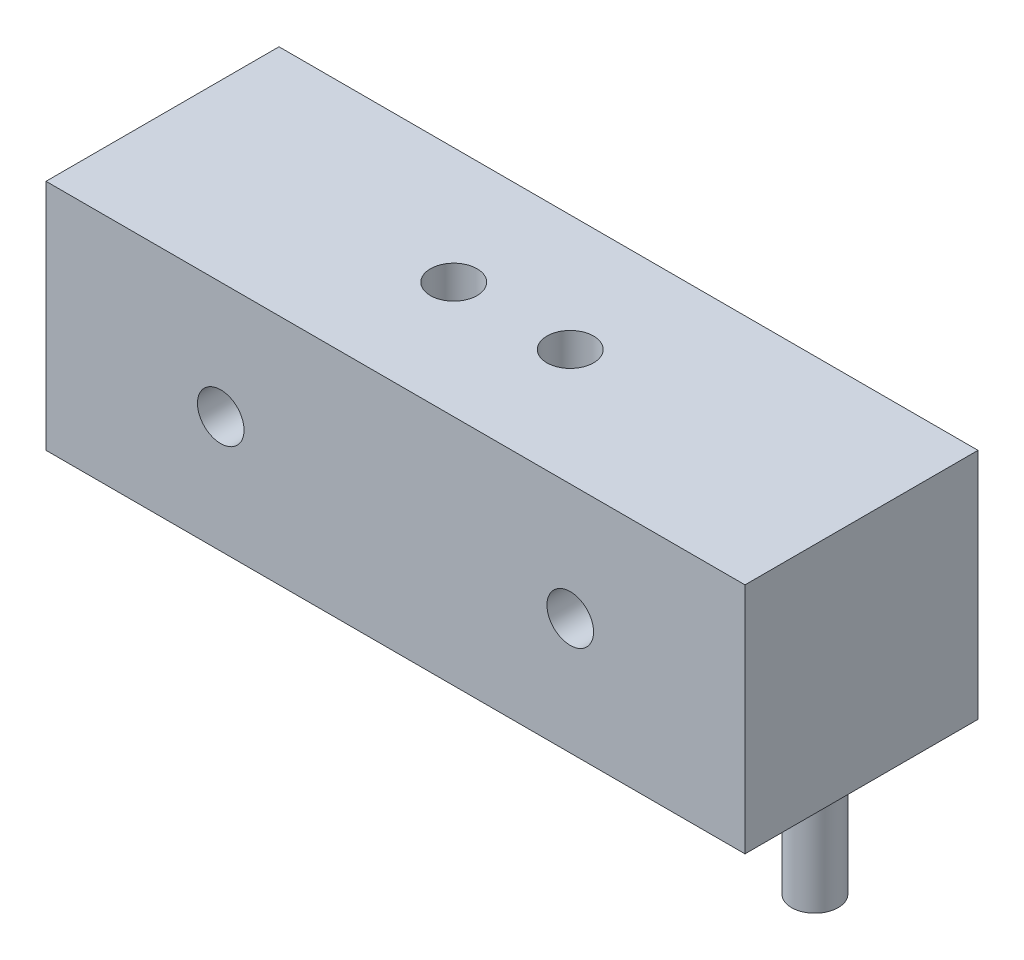
SolidWorks part; units mm, degrees
material "ABS"
ref_plane "Front Plane" through (0, 0, 0) normal (0, 0, 1) x (1, 0, 0)
ref_plane "Top Plane" through (0, 0, 0) normal (0, 1, 0) x (1, 0, 0)
ref_plane "Right Plane" through (0, 0, 0) normal (1, 0, 0) x (0, 0, -1)
sketch "Sketch1" plane through (0, 0, 0) normal (0, 0, 1) x (1, 0, 0)
  line L1 (-15, 5) -> (15, 5)
  line L2 (-15, 5) -> (-15, -5)
  line L3 (-15, -5) -> (15, -5)
  line L4 (15, 5) -> (15, -5)
  line L5 (-15, 5) -> (15, -5) construction
  line L6 (-15, -5) -> (15, 5) construction
  point P0 (0, 0)
  dimension "D1" = 10
  dimension "D2" = 30
extrude "Boss-Extrude1" add sketch "Sketch1" along normal blind 10 contours L1 L4 L3 L2
sketch "Sketch2" plane through (0, 0, 10) normal (0, 0, 1) x (1, 0, 0)
  line L0 (-7.5, 0) -> (7.5, 0) construction
  line L1 (0, 5) -> (0, -5) construction
  line L2 (-15, 5) -> (15, 5) construction
  line L3 (-15, -5) -> (15, -5) construction
  circle A0 centre (-7.5, 0) radius 1
  circle A1 centre (7.5, 0) radius 1
  point P11 (0, 0)
  dimension "D2" = 2
  dimension "D3" = 2
  dimension "D1" = 5
  dimension "D4" = 15
extrude "Cut-Extrude1" cut sketch "Sketch2" against normal through all
sketch "Sketch3" plane through (0, -5, 0) normal (0, -1, 0) x (1, 0, 0)
  line L0 (-15, 5) -> (15, 5) construction
  line L1 (-15, 10) -> (-15, 0) construction
  line L2 (15, 10) -> (15, 0) construction
  circle A0 centre (13, 5) radius 1
  dimension "D1" = 2
  dimension "D2" = 2
sketch "Sketch4" plane through (0, 5, 0) normal (0, 1, 0) x (1, 0, 0)
  line L0 (-2.5, -5) -> (2.5, -5) construction
  line L1 (0, 0) -> (0, -10) construction
  line L2 (-15, 0) -> (15, 0) construction
  line L3 (-15, -10) -> (15, -10) construction
  line L4 (-15, -5) -> (15, -5) construction
  line L5 (-15, -10) -> (-15, 0) construction
  line L6 (15, -10) -> (15, 0) construction
  circle A0 centre (-2.5, -5) radius 1
  circle A1 centre (2.5, -5) radius 1
  point P11 (0, -5)
  dimension "D2" = 2
  dimension "D3" = 2
  dimension "D1" = 5
extrude "Cut-Extrude3" cut sketch "Sketch4" against normal through all
extrude "Boss-Extrude2" add sketch "Sketch3" along normal blind 5
